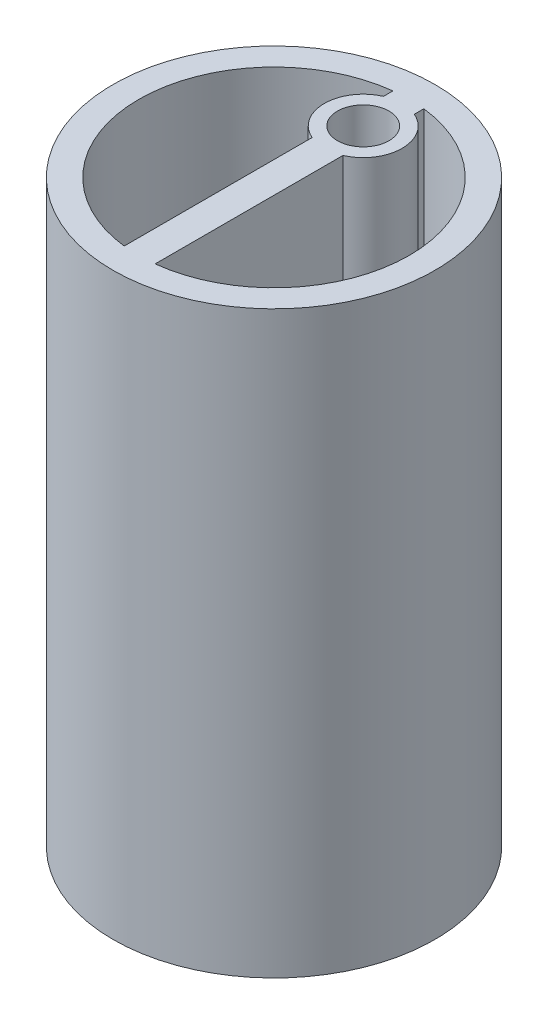
SolidWorks part; units mm, degrees
ref_plane "Front Plane" through (0, 0, 0) normal (0, 0, 1) x (1, 0, 0)
ref_plane "Top Plane" through (0, 0, 0) normal (0, 1, 0) x (1, 0, 0)
ref_plane "Right Plane" through (0, 0, 0) normal (1, 0, 0) x (0, 0, -1)
sketch "Sketch1" plane through (0, 0, 0) normal (0, 1, 0) x (1, 0, 0)
  circle A0 centre (0, 0) radius 12.5
  circle A1 centre (0, 0) radius 10.5
  dimension "D1" = 25
  dimension "D2" = 21
extrude "Boss-Extrude1" add sketch "Sketch1" along normal blind 45
sketch "Sketch3" plane through (0, 45, 0) normal (0, 1, 0) x (1, 0, 0)
  line L1 (-1.2, 11.5946) -> (1.2, 11.5946)
  line L2 (-1.2, 11.5946) -> (-1.2, -11.406)
  line L3 (-1.2, -11.406) -> (1.2, -11.406)
  line L4 (1.2, 11.5946) -> (1.2, -11.406)
  dimension "D1" = 1.2
  dimension "D2" = 1.2
extrude "Boss-Extrude3" add sketch "Sketch3" against normal through all
sketch "Sketch4" plane through (0, 45, 0) normal (0, 1, 0) x (1, 0, 0)
  circle A0 centre (0, 6.9285) radius 3.0196
  point P2 (0, 6.9285)
extrude "Boss-Extrude4" add sketch "Sketch4" against normal through all
sketch "Sketch5" plane through (0, 45, 0) normal (0, 1, 0) x (1, 0, 0)
  circle A0 centre (0, 6.9285) radius 2
  arc A1 (1.2, 4.1575) -> (1.2, 9.6994) centre (0, 6.9285) ccw construction
  dimension "D1" = 4
extrude "Cut-Extrude1" cut sketch "Sketch5" against normal through all
